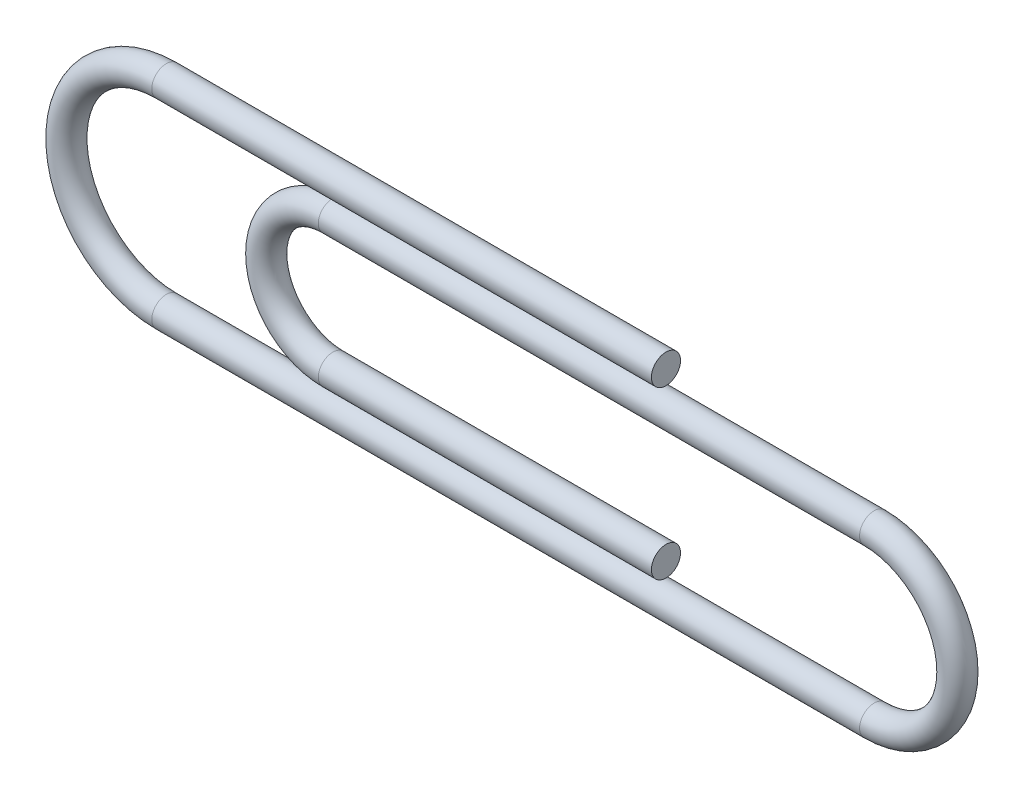
SolidWorks part; units mm, degrees
material "1060 Alloy"
ref_plane "Front Plane" through (0, 0, 0) normal (0, 0, 1) x (1, 0, 0)
ref_plane "Top Plane" through (0, 0, 0) normal (0, 1, 0) x (1, 0, 0)
ref_plane "Right Plane" through (0, 0, 0) normal (1, 0, 0) x (0, 0, -1)
sketch "Sketch1" plane through (0, 0, 0) normal (0, 0, 1) x (1, 0, 0)
  line L0 (0, 0) -> (-50.8, 0)
  line L1 (-50.8, 20.32) -> (31.75, 20.32)
  line L2 (31.75, -5.08) -> (-76.2, -5.08)
  line L3 (-76.2, 25.4) -> (0, 25.4)
  arc A0 (-50.8, 0) -> (-50.8, 20.32) centre (-50.8, 10.16) cw
  arc A1 (31.75, 20.32) -> (31.75, -5.08) centre (31.75, 7.62) cw
  arc A2 (-76.2, -5.08) -> (-76.2, 25.4) centre (-76.2, 10.16) cw
  point P11 (0, 0)
  dimension "D4" = 10.16
  dimension "D5" = 15.24
  dimension "D6" = 12.7
  dimension "D1" = 50.8
  dimension "D2" = 31.75
  dimension "D3" = 76.2
sketch "Sketch2" plane through (0, 0, 0) normal (1, 0, 0) x (0, 0, -1)
  circle A0 centre (0, 0) radius 2.2225
  dimension "D1" = 4.445
sweep "Sweep1" add profiles "Sketch2" path "Sketch1"
